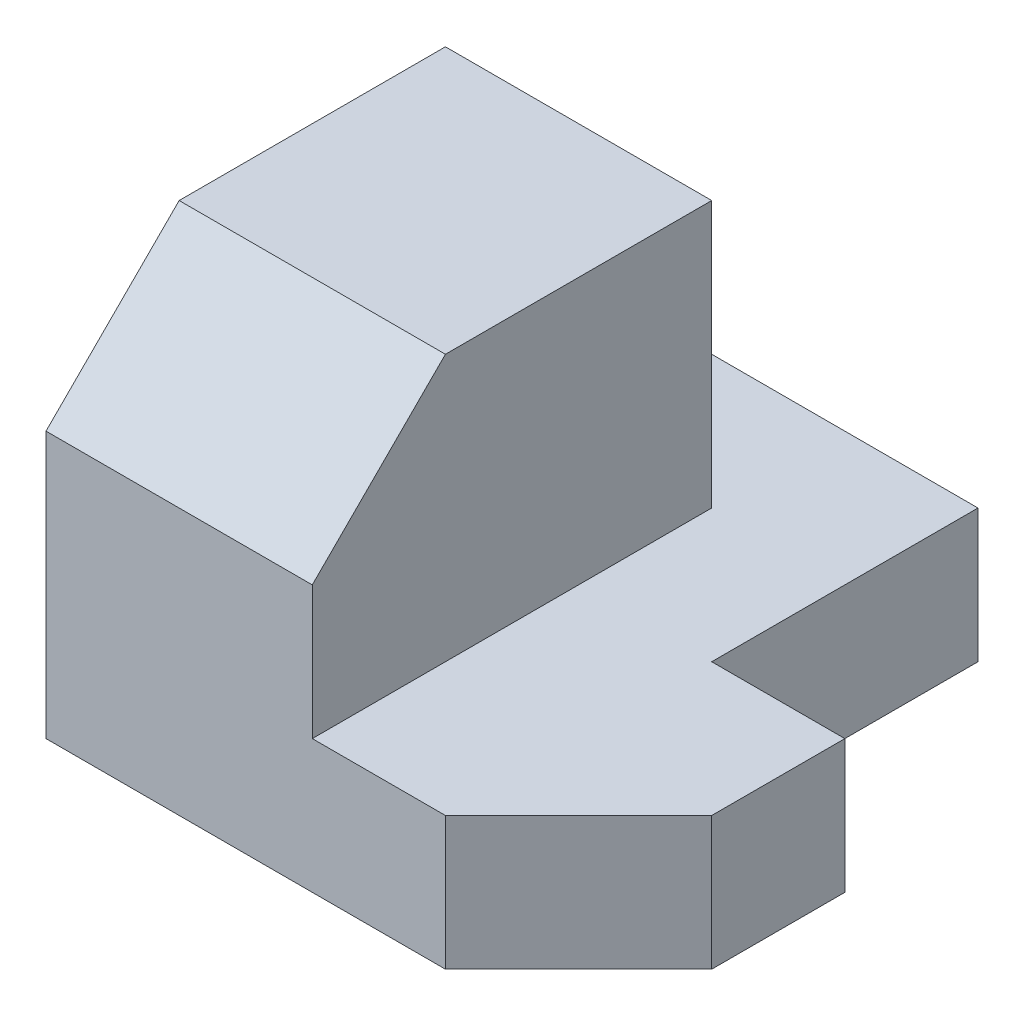
SolidWorks part; units mm, degrees
ref_plane "前基準面" through (0, 0, 0) normal (0, 0, 1) x (1, 0, 0)
ref_plane "上基準面" through (0, 0, 0) normal (0, 1, 0) x (1, 0, 0)
ref_plane "右基準面" through (0, 0, 0) normal (1, 0, 0) x (0, 0, -1)
sketch "草圖1" plane through (0, 0, 0) normal (0, 1, 0) x (1, 0, 0)
  line L0 (15, 20) -> (15, 10)
  line L1 (0, 0) -> (15, 0)
  line L2 (0, 0) -> (0, 20)
  line L3 (0, 20) -> (15, 20)
  line L4 (20, 5) -> (20, 10)
  line L5 (15, 10) -> (20, 10)
  line L6 (20, 5) -> (15, 0)
  dimension "D1" = 15
  dimension "D2" = 20
  dimension "D3" = 10
  dimension "D4" = 5
  dimension "D5" = 5
  dimension "D6" = 5
extrude "填料-伸長1" add sketch "草圖1" along normal blind 5
sketch "草圖2" plane through (0, 0, 0) normal (-1, 0, 0) x (0, 0, 1)
  line L0 (-15, 5) -> (-15, 15)
  line L1 (-15, 15) -> (-5, 15)
  line L2 (-5, 15) -> (0, 10)
  line L3 (0, 10) -> (0, 5)
  line L4 (-20, 5) -> (0, 5) construction
  line L5 (0, 5) -> (-15, 5)
  line L6 (-20, 5) -> (-20, 0) construction
  point P3 (0, 0)
  point P9 (-16.1322, 5)
  dimension "D1" = 10
  dimension "D2" = 10
  dimension "D3" = 5
  dimension "D4" = 5
  dimension "D5" = 5
extrude "填料-伸長2" add sketch "草圖2" against normal blind 10
